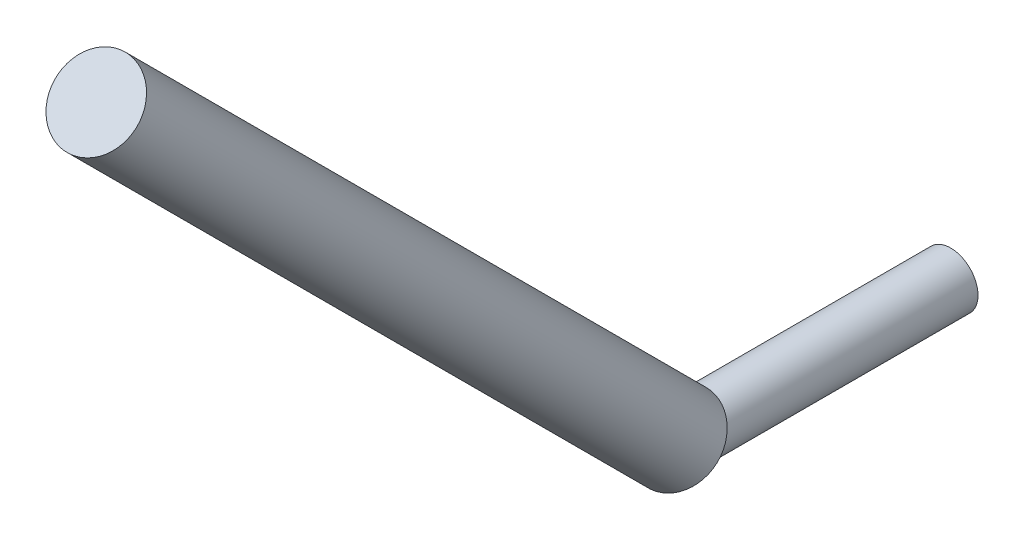
SolidWorks part; units mm, degrees
ref_plane "Front Plane" through (0, 0, 0) normal (0, 0, 1) x (1, 0, 0)
ref_plane "Top Plane" through (0, 0, 0) normal (0, 1, 0) x (1, 0, 0)
ref_plane "Right Plane" through (0, 0, 0) normal (1, 0, 0) x (0, 0, -1)
sketch "Sketch1" plane through (0, 0, 0) normal (0, 0, 1) x (1, 0, 0)
  circle A0 centre (0, 0) radius 2
  dimension "D1" = 4
extrude "Boss-Extrude1" add sketch "Sketch1" against normal blind 20
sketch "Sketch4" plane through (0, 0, 0) normal (1, 0, 0) x (0, 0, -1)
  line L0 (0, 0) -> (-42.4264, 42.4264) construction
  line L1 (0, 0) -> (2.1213, 2.1213)
  line L2 (2.1213, 2.1213) -> (-40.3051, 44.5477)
  line L3 (-40.3051, 44.5477) -> (-42.4264, 42.4264)
  line L4 (0, 0) -> (-42.4264, 42.4264)
  line L5 (0, 0) -> (-24.8942, 0) construction
  dimension "D1" = 60
  dimension "D2" = 3
  dimension "D3" = 45
revolve "Revolve1" add sketch "Sketch4" angle 360 about L0
